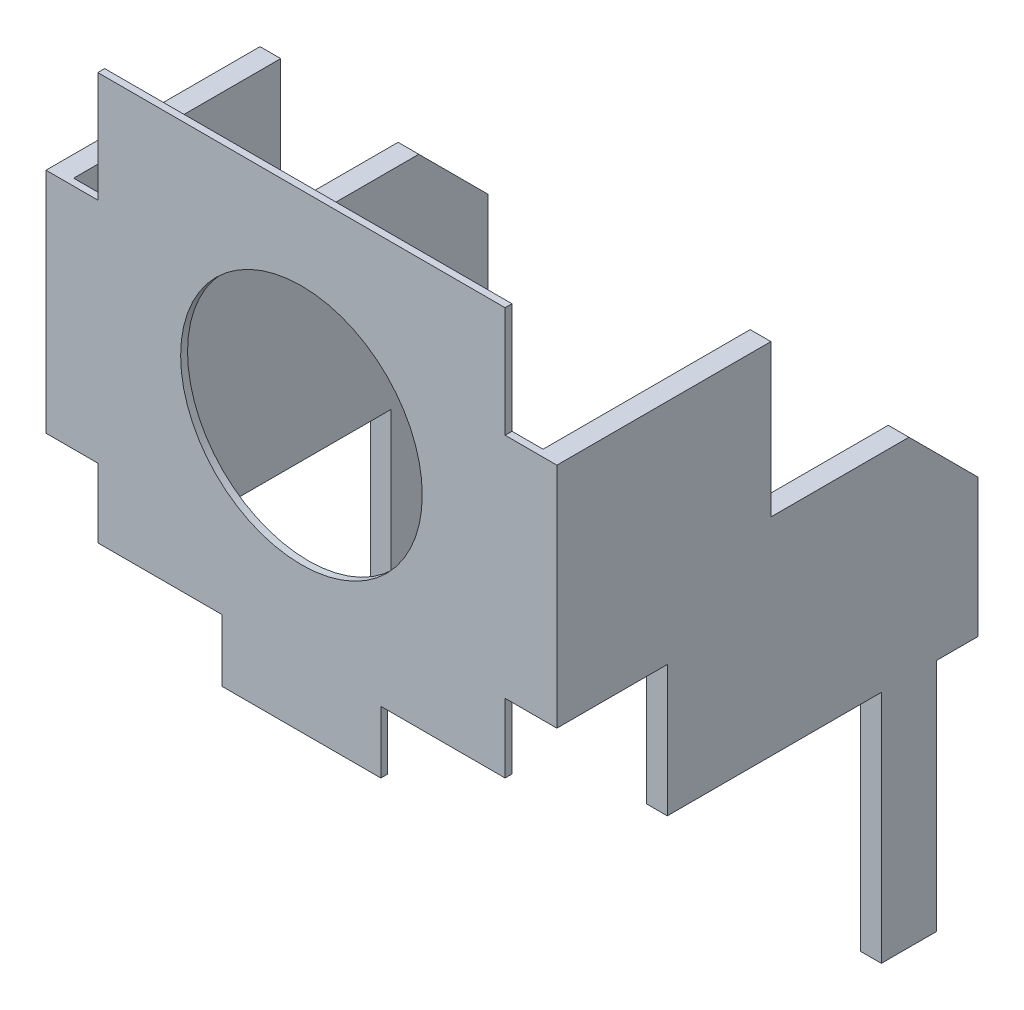
SolidWorks part; units mm, degrees
ref_plane "Front" through (0, 0, 0) normal (0, 0, 1) x (1, 0, 0)
ref_plane "Top" through (0, 0, 0) normal (0, 1, 0) x (1, 0, 0)
ref_plane "Right" through (0, 0, 0) normal (1, 0, 0) x (0, 0, -1)
sketch "Sketch1" plane through (0, 0, 0) normal (0, 0, 1) x (1, 0, 0)
  line L0 (1.8, 0) -> (1.8, -0.9)
  line L1 (0, 0) -> (1.8, 0)
  line L2 (0, 0) -> (0, 1)
  line L3 (0, 5.9) -> (5.9, 5.9)
  line L4 (5.9, 0) -> (5.9, 1)
  line L5 (1.8, -0.9) -> (4.1, -0.9)
  line L6 (4.1, -0.9) -> (4.1, 0)
  line L7 (5.9, 4.3) -> (6.65, 4.3)
  line L8 (6.65, 4.3) -> (6.65, 1)
  line L9 (6.65, 1) -> (5.9, 1)
  line L10 (0, 4.3) -> (-0.75, 4.3)
  line L11 (-0.75, 4.3) -> (-0.75, 1)
  line L12 (-0.75, 1) -> (0, 1)
  line L13 (4.1, 0) -> (5.9, 0)
  line L14 (5.9, 4.3) -> (5.9, 5.9)
  line L15 (0, 4.3) -> (0, 5.9)
  line L16 (0, 0) -> (5.9, 5.9) construction
  line L17 (5.9, 0) -> (0, 5.9) construction
  circle A0 centre (2.95, 2.95) radius 1.75
  point P15 (2.95, 5.9)
  point P18 (2.95, -0.9)
  dimension "D10" = 3.5
  dimension "D1" = 5.9
  dimension "D2" = 5.9
  dimension "D3" = 1.6
  dimension "D4" = 1.9
  dimension "D5" = 0.9
  dimension "D6" = 7.4
  dimension "D8" = 2.3
  dimension "D9" = 2.95
  dimension "D7" = 3.7
extrude "Boss-Extrude1" add sketch "Sketch1" along normal blind 0.1
sketch "Sketch2" plane through (0, 0, 0) normal (0, 0, -1) x (-1, 0, 0)
  line L0 (-5.9, 1) -> (-6.65, 1) construction
  line L1 (-6.65, 4.3) -> (-6.35, 4.3)
  line L2 (-6.65, 4.3) -> (-6.65, 1)
  line L3 (-6.65, 1) -> (-6.35, 1)
  line L4 (-6.35, 4.3) -> (-6.35, 1)
  line L5 (0, 4.3) -> (0.75, 4.3) construction
  line L6 (0.75, 1) -> (0.45, 1)
  line L7 (0.75, 1) -> (0.75, 4.3)
  line L8 (0.75, 4.3) -> (0.45, 4.3)
  line L9 (0.45, 1) -> (0.45, 4.3)
  dimension "D1" = 0.3
  dimension "D2" = 0.3
extrude "Boss-Extrude2" add sketch "Sketch2" along normal blind 3
sketch "Sketch3" plane through (0, 0, -3) normal (0, 0, -1) x (-1, 0, 0)
  line L0 (0.75, 1) -> (0.75, 4.3) construction
  line L1 (0.75, 2.1) -> (0.45, 2.1)
  line L2 (0.75, 2.1) -> (0.75, -0.9)
  line L3 (0.75, -0.9) -> (0.45, -0.9)
  line L4 (0.45, 2.1) -> (0.45, -0.9)
  line L5 (-6.65, 4.3) -> (-6.65, 1) construction
  line L6 (-6.65, 2.1) -> (-6.35, 2.1)
  line L7 (-6.65, 2.1) -> (-6.65, -0.9)
  line L8 (-6.65, -0.9) -> (-6.35, -0.9)
  line L9 (-6.35, 2.1) -> (-6.35, -0.9)
  line L10 (0.45, 4.3) -> (0.45, 1) construction
  line L11 (-6.35, 1) -> (-6.35, 4.3) construction
  line L12 (-1.8, -0.9) -> (-4.1, -0.9) construction
  dimension "D1" = 3
extrude "Boss-Extrude3" add sketch "Sketch3" along normal blind 3 and the other way blind 1.5
sketch "Sketch5" plane through (0, 0, 0) normal (1, 0, 0) x (0, 0, -1)
  line L0 (5, 2.1) -> (6, 1.1)
  line L1 (3, 2.1) -> (6, 2.1) construction
  line L2 (6, -0.9) -> (6, 2.1) construction
  line L3 (5, 2.1) -> (6, 2.1)
  line L4 (6, 2.1) -> (6, 1.1)
  point P6 (6, 1.2919)
  dimension "D1" = 1
  dimension "D2" = 1
extrude "Cut-Extrude1" cut sketch "Sketch5" against normal through all both and the other way through all
sketch "Sketch6" plane through (0, -0.9, 0) normal (0, -1, 0) x (1, 0, 0)
  line L0 (-0.75, -1.5) -> (-0.75, -6) construction
  line L1 (-0.75, -5.4) -> (-0.45, -5.4)
  line L2 (-0.75, -5.4) -> (-0.75, -4.6)
  line L3 (-0.75, -4.6) -> (-0.45, -4.6)
  line L4 (-0.45, -5.4) -> (-0.45, -4.6)
  line L5 (-0.45, -1.5) -> (-0.45, -6) construction
  line L6 (6.35, -1.5) -> (6.35, -6) construction
  line L7 (6.35, -5.4) -> (6.65, -5.4)
  line L8 (6.35, -5.4) -> (6.35, -4.6)
  line L9 (6.35, -4.6) -> (6.65, -4.6)
  line L10 (6.65, -5.4) -> (6.65, -4.6)
  line L11 (6.65, -1.5) -> (6.65, -6) construction
  line L12 (-0.45, -6) -> (-0.75, -6) construction
  point P16 (-0.45, -5)
  dimension "D1" = 0.8
  dimension "D2" = 1
extrude "Boss-Extrude4" add sketch "Sketch6" along normal blind 3.4
equation "\"D9@Sketch1\"=\"D1@Sketch1\"/2"
equation "\"D7@Sketch1\"=\"D6@Sketch1\"/2"
